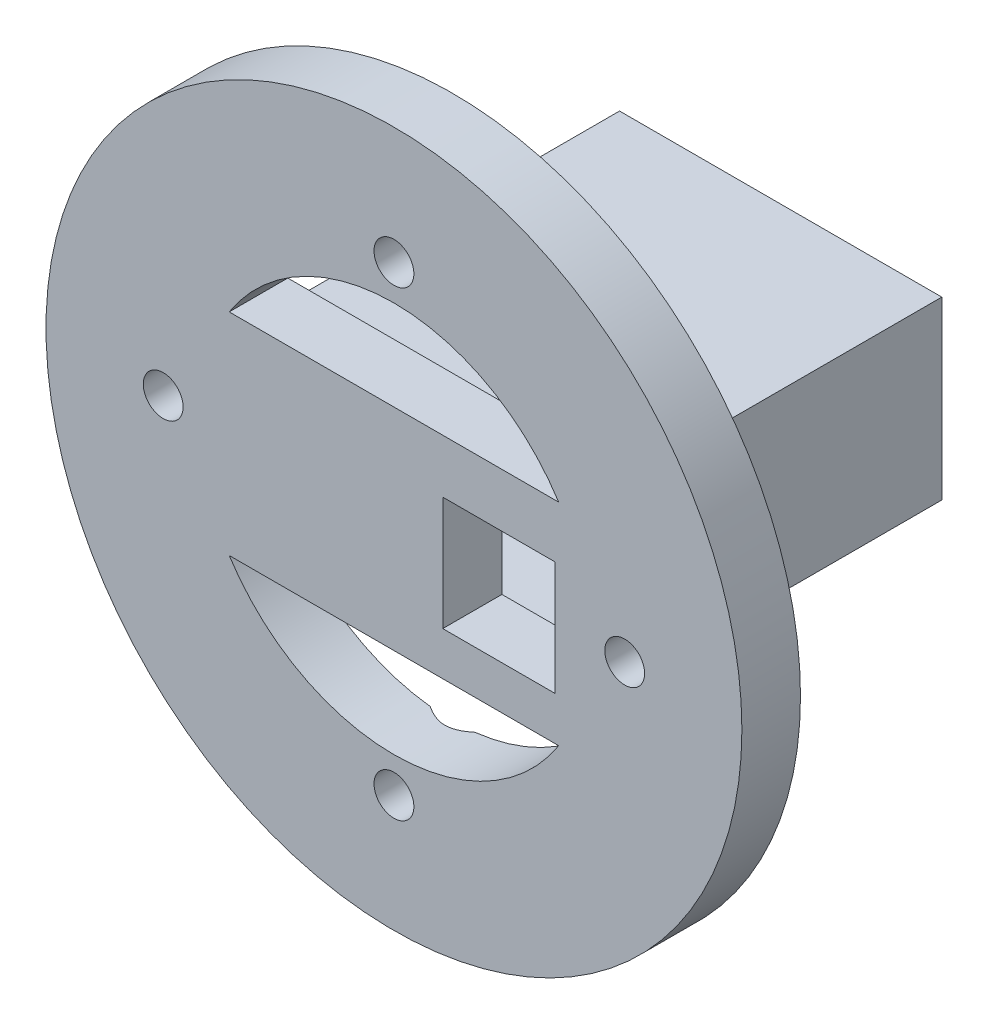
SolidWorks part; units mm, degrees
ref_plane "Front Plane" through (0, 0, 0) normal (0, 0, 1) x (1, 0, 0)
ref_plane "Top Plane" through (0, 0, 0) normal (0, 1, 0) x (1, 0, 0)
ref_plane "Right Plane" through (0, 0, 0) normal (1, 0, 0) x (0, 0, -1)
sketch "Sketch1" plane through (0, 0, 0) normal (0, 0, 1) x (-1, 0, 0)
  line L1 (-14.0585, 9) -> (14.0585, 9)
  line L3 (-14.0585, -9) -> (14.0585, -9)
  line L5 (-14.693, 7.9219) -> (14.693, -7.9219) construction
  line L6 (-14.693, -7.9219) -> (14.693, 7.9219) construction
  circle A0 centre (0, 0) radius 29.6925
  circle A1 centre (0, 0) radius 22.6925
  circle A2 centre (0, 0) radius 16.6925
  circle A3 centre (0, 0) radius 19.6925
  point P5 (0, 16.6925)
  point P7 (16.6925, 0)
  point P9 (0, -16.6925)
  point P11 (-16.6925, 0)
  dimension "D1" = 6
  dimension "D2" = 45.3851
  dimension "D3" = 3
  dimension "D4" = 7
  dimension "D5" = 33.3851
  dimension "D7" = 59.3851
  dimension "D6" = 18
extrude "Boss-Extrude1" add sketch "Sketch1" along normal blind 5 contours L3 A2 L1 | A3 A2 | A1 A3 | A0 A1
sketch "Sketch4" plane through (0, 0, 0) normal (0, 0, -1) x (1, 0, 0)
  line L1 (-14.0585, 10.3647) -> (14.0585, 10.3647)
  line L3 (-14.0585, -7.6353) -> (14.0585, -7.6353)
  line L5 (-14.693, 7.9219) -> (14.693, -7.9219) construction
  line L6 (-14.693, -7.9219) -> (14.693, 7.9219) construction
  circle A0 centre (0, 0) radius 29.6925
  circle A1 centre (0, 0) radius 22.6925
  circle A3 centre (0, 0) radius 19.6925
  point P22 (0, 19.6925)
  point P24 (0, -19.6925)
  point P26 (19.6925, 0)
  point P28 (-19.6925, 0)
  dimension "D2" = 45.3851
  dimension "D3" = 3
  dimension "D4" = 7
  dimension "D6" = 18
sketch "Sketch9" plane through (0, 0, 0) normal (0, 1, 0) x (1, 0, 0)
  line L1 (-13.75, 0) -> (13.75, 0)
  line L7 (14.693, 0) -> (-14.693, 0) construction
  line L8 (-13.75, 28) -> (13.75, 0) construction
  line L9 (-13.75, 0) -> (13.75, 28) construction
  line L10 (13.75, 0) -> (13.75, 28)
  line L11 (-13.75, 28) -> (13.75, 28)
  line L12 (-13.75, 0) -> (-13.75, 28)
  point P0 (0, 14)
  point P18 (0, 8.5)
  dimension "D1" = 27.5
  dimension "D2" = 28
  dimension "D3" = 28
extrude "Boss-Extrude2" add sketch "Sketch9" along normal mid plane 15
sketch "Sketch10" plane through (0, 0, 0) normal (0, 1, 0) x (1, 0, 0)
  line L0 (-13.75, 28) -> (13.75, 28)
  line L1 (-13.75, 28) -> (-13.75, 0.1022)
  line L2 (13.75, 28) -> (13.75, 0.1022)
  line L3 (-13.75, 0.1022) -> (13.75, 0.1022)
  line L4 (-13.75, 28) -> (13.75, 0.1022) construction
  line L5 (-13.75, 0.1022) -> (13.75, 28) construction
  line L6 (-11.75, 0.05) -> (11.75, 0.05)
  line L7 (-11.75, 0.05) -> (-11.75, 25.5)
  line L8 (11.75, 0.05) -> (11.75, 25.5)
  line L9 (-11.75, 25.5) -> (11.75, 25.5)
  point P0 (0, 0.05)
  dimension "D1" = 25.45
  dimension "D2" = 23.5
  dimension "D3" = 2.5
sketch "Sketch11" plane through (0, 0, 5) normal (0, 0, 1) x (1, 0, 0)
  line L0 (13.75, -5.2927) -> (13.75, 4.425)
  line L5 (13.75, -5.2927) -> (4.1647, -5.2927)
  line L6 (13.75, 4.425) -> (4.1647, 4.425)
  line L7 (4.1647, -5.2927) -> (4.1647, 4.425)
  line L8 (13.75, 7.5) -> (13.75, -7.5) construction
  dimension "D1" = 9.5853
  dimension "D2" = 9.7177
extrude "Cut-Extrude1" cut sketch "Sketch10" against normal mid plane 12.2 contours L8 L9 L7 L6
sketch "Sketch12" plane through (0, 0, -28) normal (0, 0, 1) x (1, 0, 0)
  line L0 (13.75, 7.5) -> (13.75, -7.5) construction
  line L1 (-2.25, 5.5) -> (9.75, 5.5)
  line L2 (-2.25, 5.5) -> (-2.25, -5.5)
  line L3 (-2.25, -5.5) -> (9.75, -5.5)
  line L4 (9.75, 5.5) -> (9.75, -5.5)
  line L5 (-2.25, 5.5) -> (9.75, -5.5) construction
  line L6 (-2.25, -5.5) -> (9.75, 5.5) construction
  line L7 (13.75, 7.5) -> (-13.75, 7.5) construction
  line L8 (13.75, -7.5) -> (-13.75, -7.5) construction
  point P0 (0, 0)
  dimension "D1" = 2
  dimension "D2" = 4
  dimension "18.5" = 12
  dimension "D3" = 2
extrude "Cut-Extrude2" cut sketch "Sketch12" along normal blind 3 contours L3 L4 L1 L2
extrude "Cut-Extrude3" cut sketch "Sketch11" against normal up to surface (5.05 mm away) contours L6 L7 L5 L0 up to face at (0, 0, -0.05)
hole_wizard "CSK for M3 Flat Head Machine Screw1" positions "Sketch4" profile "Sketch13" countersink size "M3" standard "ANSI Metric"
sketch "Sketch13" plane through (-19.6925, 0, 0) normal (1, 0, 0) x (0, 1, 0)
  line L0 (0, 0) -> (0, 13.0215)
  line L1 (0, 13.0215) -> (1.7, 12)
  line L2 (1.7, 12) -> (1.7, 1.95)
  line L3 (1.7, 1.95) -> (3.65, 0)
  line L5 (3.65, 0) -> (0, 0)
  line L6 (-1.7, 1.95) -> (-3.65, 0) construction
  line L10 (0, 13.0215) -> (-1.7, 12) construction
  line L11 (0, -6.35) -> (0, 107.95) construction
  dimension "Hole Dia." = 3.4
  dimension "Hole Depth" = 12
  dimension "Near C'Sink Dia." = 7.3
  dimension "Near C'Sink Angle" = 90
  dimension "Drill Angle" = 118
sketch "Sketch14" plane through (0, 0, -28) normal (0, 0, -1) x (-1, 0, 0)
  circle A0 centre (0, 0) radius 15.6625
  dimension "D1" = 31.3249
